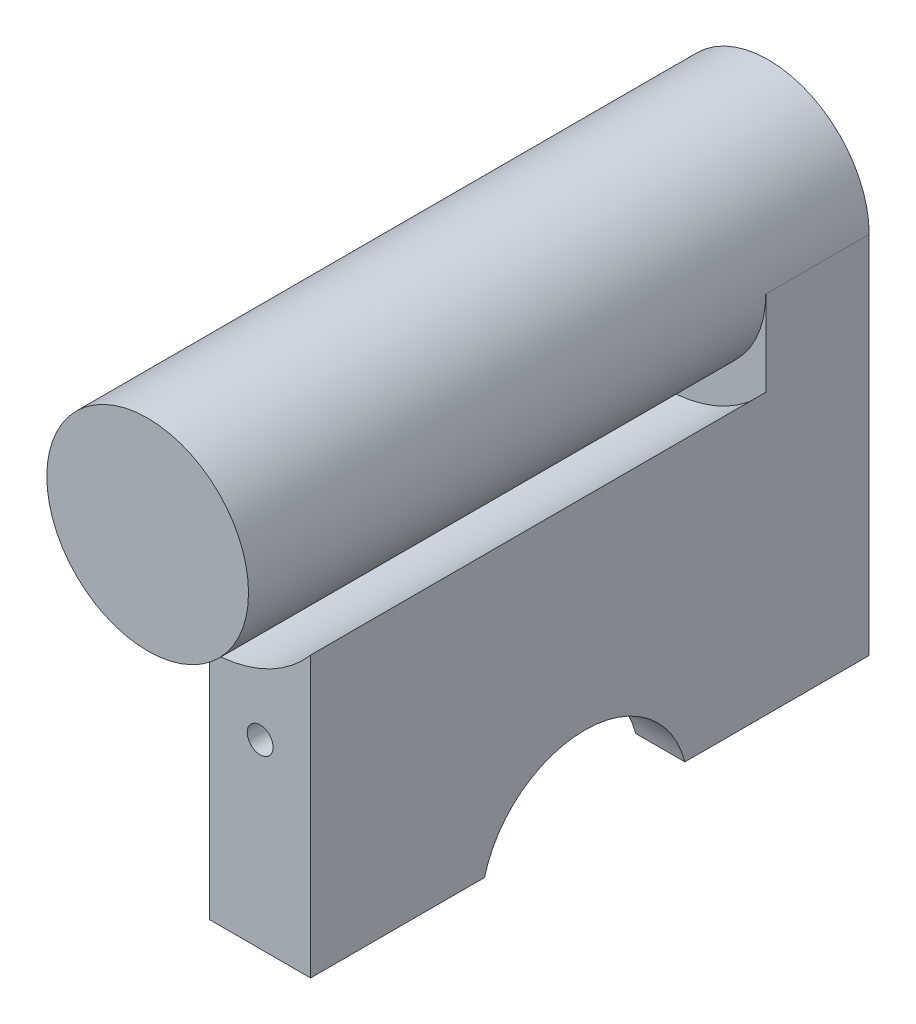
SolidWorks part; units mm, degrees
ref_plane "정면" through (0, 0, 0) normal (0, 0, 1) x (1, 0, 0)
ref_plane "윗면" through (0, 0, 0) normal (0, 1, 0) x (1, 0, 0)
ref_plane "우측면" through (0, 0, 0) normal (1, 0, 0) x (0, 0, -1)
sketch "스케치1" plane through (0, 0, 0) normal (0, 0, 1) x (1, 0, 0)
  circle A0 centre (0, 0) radius 1.95
  dimension "D1" = 3.9
extrude "보스-돌출1" add sketch "스케치1" along normal blind 12
sketch "스케치4" plane through (0, 0, 0) normal (1, 0, 0) x (0, 0, -1)
  line L5 (-2, 1.95) -> (0, 1.95)
  line L6 (-2, 1.95) -> (-2, -7.05)
  line L7 (-2, -7.05) -> (0, -7.05)
  line L8 (0, 1.95) -> (0, -7.05)
  line L9 (-2, 1.95) -> (0, -7.05) construction
  line L10 (-2, -7.05) -> (0, 1.95) construction
  point P0 (-1, -2.55)
  dimension "D1" = 2
  dimension "D2" = 9
extrude "보스-돌출2" add sketch "스케치4" along normal blind 1.95
sketch "스케치8" plane through (0, 0, 2) normal (0, 0, 1) x (1, 0, 0)
  line L0 (0, -1.95) -> (0, -7.05)
  line L1 (0, -7.05) -> (1.95, -7.05)
  line L2 (1.95, -7.05) -> (1.95, -1.6432)
  line L3 (0, -2.55) -> (0, -7.05)
  line L4 (1.95, -7.05) -> (1.95, -1.6432)
  line L5 (1.95, 0) -> (1.95, -7.05) construction
  line L6 (0, -1.95) -> (0, -7.05) construction
  circle A0 centre (0, 0) radius 1.95 construction
  circle A2 centre (0, 0) radius 1.95
  circle A3 centre (0, 0) radius 1.95
  circle A5 centre (0, 0) radius 2.55
  dimension "D2" = 5.1
  dimension "D1" = 0
extrude "보스-돌출4" add sketch "스케치8" along normal blind 8.8
sketch "스케치9" plane through (0, 0, 0) normal (-1, 0, 0) x (0, 0, 1)
  line L1 (12, -1.95) -> (12, 1.95) construction
  line L6 (10.8, -7.05) -> (0, -7.05) construction
  circle A0 centre (5.5, -7.55) radius 2
  dimension "D1" = 4
  dimension "D2" = 6.5
  dimension "D3" = 0.5
extrude "컷-돌출2" cut sketch "스케치9" against normal blind 17
sketch "스케치12" plane through (0, 0, 2) normal (0, 0, 1) x (1, 0, 0)
  line L0 (0, 1.95) -> (1.95, 1.95)
  line L1 (1.95, 1.95) -> (1.95, 0)
  circle A1 centre (0, 0) radius 1.95
  line M7 (1.95, 1.95) -> (0, 1.95)
  arc M8 (0, 1.95) -> (1.95, 0) centre (0, 0) cw
  line M9 (1.95, 0) -> (1.95, 1.95)
sketch "스케치13" plane through (0, 0, 0) normal (-1, 0, 0) x (0, 0, 1)
  line L0 (10.8, -7.05) -> (7.4365, -7.05) construction
  line L2 (0, -7.05) -> (0, -1.95) construction
  circle A0 centre (5.505, -7.55) radius 2.75
  dimension "D1" = 0.5
  dimension "D2" = 5.5
  dimension "D3" = 5.505
extrude "컷-돌출6" cut sketch "스케치13" against normal blind 1
extrude "컷-돌출7" cut sketch "스케치12" against normal through all contours M9 M7 M8
sketch "스케치14" plane through (0, 0, 0) normal (0, 0, -1) x (-1, 0, 0)
  line L0 (0, -7.05) -> (0, -1.95) construction
  line L2 (-1.95, -7.05) -> (0, -7.05) construction
  circle A0 centre (-0.975, -3.55) radius 0.25
  dimension "D1" = 0.975
  dimension "D2" = 0.5
  dimension "D3" = 3.5
extrude "컷-돌출8" cut sketch "스케치14" against normal through all
equation "\"15.9.00mm\"= 15.9"
equation "\"D1\" = 1.50mm"
